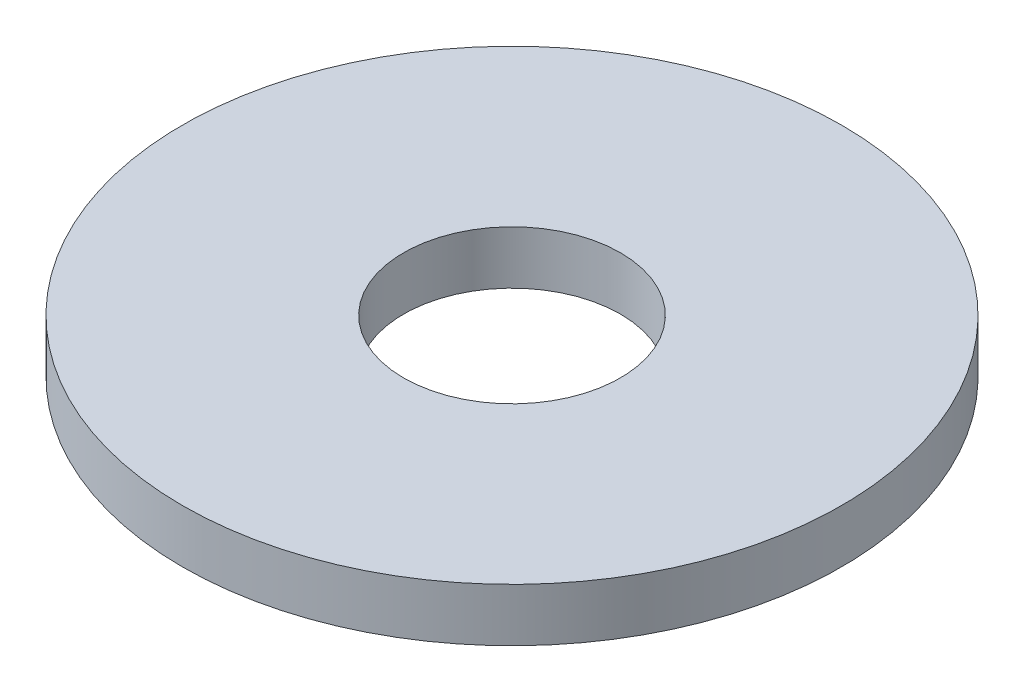
SolidWorks part; units mm, degrees
ref_plane "Front Plane" through (0, 0, 0) normal (0, 0, 1) x (1, 0, 0)
ref_plane "Top Plane" through (0, 0, 0) normal (0, 1, 0) x (1, 0, 0)
ref_plane "Right Plane" through (0, 0, 0) normal (1, 0, 0) x (0, 0, -1)
sketch "Sketch1" plane through (0, 0, 0) normal (0, 1, 0) x (1, 0, 0)
  circle A0 centre (0, 0) radius 31
  circle A1 centre (0, 0) radius 10.2
extrude "Revolved_Equivalent_Extrude" add sketch "Sketch1" along normal blind 5
equation "\"ValveDiameter\" = 50mm"
equation "\"MotorGearTeeth\" = 40"
equation "\"OutputGearTeeth\" = 80"
equation "\"GearModule\" = 1.5mm"
equation "\"PressureAngle\" = 20deg"
equation "\"GearCenterDistance\" = 90mm"
equation "\"GearWidth\" = 18mm"
equation "\"OutputShaftDiameter\" = 20mm"
equation "\"BearingOD\" = 47mm"
equation "\"BearingWidth\" = 14mm"
equation "\"PlateThickness\" = 6mm"
equation "\"ValveRotation\" = 90deg"
